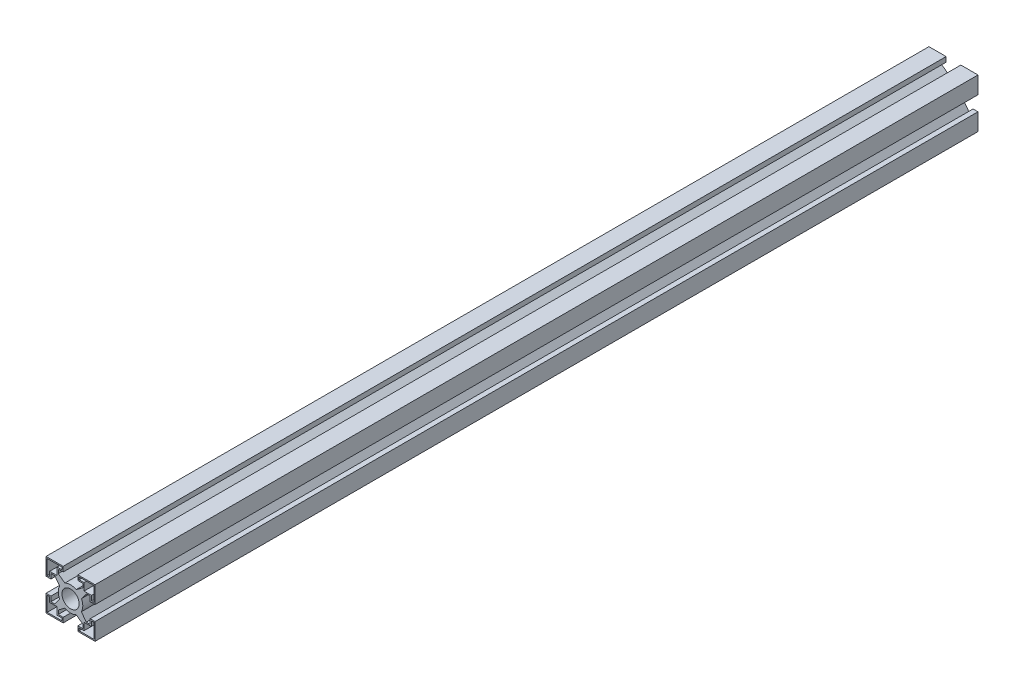
SolidWorks part; units mm, degrees
ref_plane "Plan de face" through (0, 0, 0) normal (0, 0, 1) x (1, 0, 0)
ref_plane "Plan de dessus" through (0, 0, 0) normal (0, 1, 0) x (1, 0, 0)
ref_plane "Plan de droite" through (0, 0, 0) normal (1, 0, 0) x (0, 0, -1)
sketch "Esquisse1" plane through (0, 0, 0) normal (0, 0, 1) x (1, 0, 0)
  line L5 (-5, 5) -> (-5, 1.5)
  line L22 (5, -5) -> (-5, -5) construction
  line L23 (5, -5) -> (5, 5) construction
  line L24 (5, 5) -> (-5, 5) construction
  line L25 (-5, -5) -> (-5, 5) construction
  line L26 (5, -5) -> (-5, 5) construction
  line L27 (5, 5) -> (-5, -5) construction
  line L28 (-5, 1.5) -> (-4, 1.5)
  line L29 (-4, 1.5) -> (-4, 2.5)
  line L30 (-4, 2.5) -> (-2.5, 2.5)
  line L79 (-2.5, 2.5) -> (-2.5, 4)
  line L80 (-2.5, 4) -> (-1.5, 4)
  line L82 (-1.5, 4) -> (-1.5, 5)
  line L85 (-1.5, 5) -> (-5, 5)
  line L86 (-4.75, 4.75) -> (-4.75, 1.75)
  line L87 (-4.75, 1.75) -> (-4.25, 1.75)
  line L88 (-4.25, 1.75) -> (-4.25, 2.75)
  line L89 (-4.25, 2.75) -> (-2.75, 2.75)
  line L90 (-2.75, 2.75) -> (-2.75, 4.25)
  line L92 (-2.75, 4.25) -> (-1.75, 4.25)
  line L93 (-1.75, 4.25) -> (-1.75, 4.75)
  line L94 (-1.75, 4.75) -> (-4.75, 4.75)
  line L95 (5, 5) -> (1.5, 5)
  line L96 (1.5, 5) -> (1.5, 4)
  line L97 (1.5, 4) -> (2.5, 4)
  line L98 (2.5, 4) -> (2.5, 2.5)
  line L99 (2.5, 2.5) -> (4, 2.5)
  line L100 (4, 2.5) -> (4, 1.5)
  line L101 (4, 1.5) -> (5, 1.5)
  line L102 (5, 1.5) -> (5, 5)
  line L103 (4.75, 4.75) -> (1.75, 4.75)
  line L104 (1.75, 4.75) -> (1.75, 4.25)
  line L105 (1.75, 4.25) -> (2.75, 4.25)
  line L106 (2.75, 4.25) -> (2.75, 2.75)
  line L107 (2.75, 2.75) -> (4.25, 2.75)
  line L108 (4.25, 2.75) -> (4.25, 1.75)
  line L109 (4.25, 1.75) -> (4.75, 1.75)
  line L110 (4.75, 1.75) -> (4.75, 4.75)
  line L111 (5, -5) -> (5, -1.5)
  line L112 (5, -1.5) -> (4, -1.5)
  line L113 (4, -1.5) -> (4, -2.5)
  line L114 (4, -2.5) -> (2.5, -2.5)
  line L115 (2.5, -2.5) -> (2.5, -4)
  line L116 (2.5, -4) -> (1.5, -4)
  line L117 (1.5, -4) -> (1.5, -5)
  line L118 (1.5, -5) -> (5, -5)
  line L119 (4.75, -4.75) -> (4.75, -1.75)
  line L120 (4.75, -1.75) -> (4.25, -1.75)
  line L121 (4.25, -1.75) -> (4.25, -2.75)
  line L122 (4.25, -2.75) -> (2.75, -2.75)
  line L123 (2.75, -2.75) -> (2.75, -4.25)
  line L124 (2.75, -4.25) -> (1.75, -4.25)
  line L125 (1.75, -4.25) -> (1.75, -4.75)
  line L126 (1.75, -4.75) -> (4.75, -4.75)
  line L127 (-5, -5) -> (-1.5, -5)
  line L128 (-1.5, -5) -> (-1.5, -4)
  line L129 (-1.5, -4) -> (-2.5, -4)
  line L130 (-2.5, -4) -> (-2.5, -2.5)
  line L131 (-2.5, -2.5) -> (-4, -2.5)
  line L132 (-4, -2.5) -> (-4, -1.5)
  line L133 (-4, -1.5) -> (-5, -1.5)
  line L134 (-5, -1.5) -> (-5, -5)
  line L135 (-4.75, -4.75) -> (-1.75, -4.75)
  line L136 (-1.75, -4.75) -> (-1.75, -4.25)
  line L137 (-1.75, -4.25) -> (-2.75, -4.25)
  line L138 (-2.75, -4.25) -> (-2.75, -2.75)
  line L139 (-2.75, -2.75) -> (-4.25, -2.75)
  line L140 (-4.25, -2.75) -> (-4.25, -1.75)
  line L141 (-4.25, -1.75) -> (-4.75, -1.75)
  line L142 (-4.75, -1.75) -> (-4.75, -4.75)
  line L143 (-3.2071, 2.5) -> (-2.2167, 1.156)
  line L144 (-2.5, 3.2071) -> (-1.156, 2.2167)
  line L145 (-2.2167, 1.156) -> (-1.156, 2.2167) construction
  line L146 (-2.5, 3.2071) -> (-3.2071, 2.5) construction
  line L147 (3.2071, 2.5) -> (2.2167, 1.156)
  line L148 (2.5, 3.2071) -> (1.156, 2.2167)
  line L149 (2.5, -3.2071) -> (1.156, -2.2167)
  line L150 (3.2071, -2.5) -> (2.2167, -1.156)
  line L151 (-3.2071, -2.5) -> (-2.2167, -1.156)
  line L152 (-2.5, -3.2071) -> (-1.156, -2.2167)
  circle A2 centre (0, 0) radius 1.75
  circle A3 centre (0, 0) radius 2.5
  point P73 (0, 0)
  point P78 (-2.8536, 2.8536)
  point P79 (-1.6863, 1.6863)
  point P91 (0, 0)
  dimension "D2" = 3.5
  dimension "D3" = 10
  dimension "D1" = 5
  dimension "D4" = 3.5
  dimension "D5" = 1
  dimension "D6" = 1.5
  dimension "D7" = 0.25
  dimension "D8" = 4
  dimension "D9" = 1
  dimension "D10" = 1.5
extrude "Boss.-Extru.1" add sketch "Esquisse1" along normal blind 180
